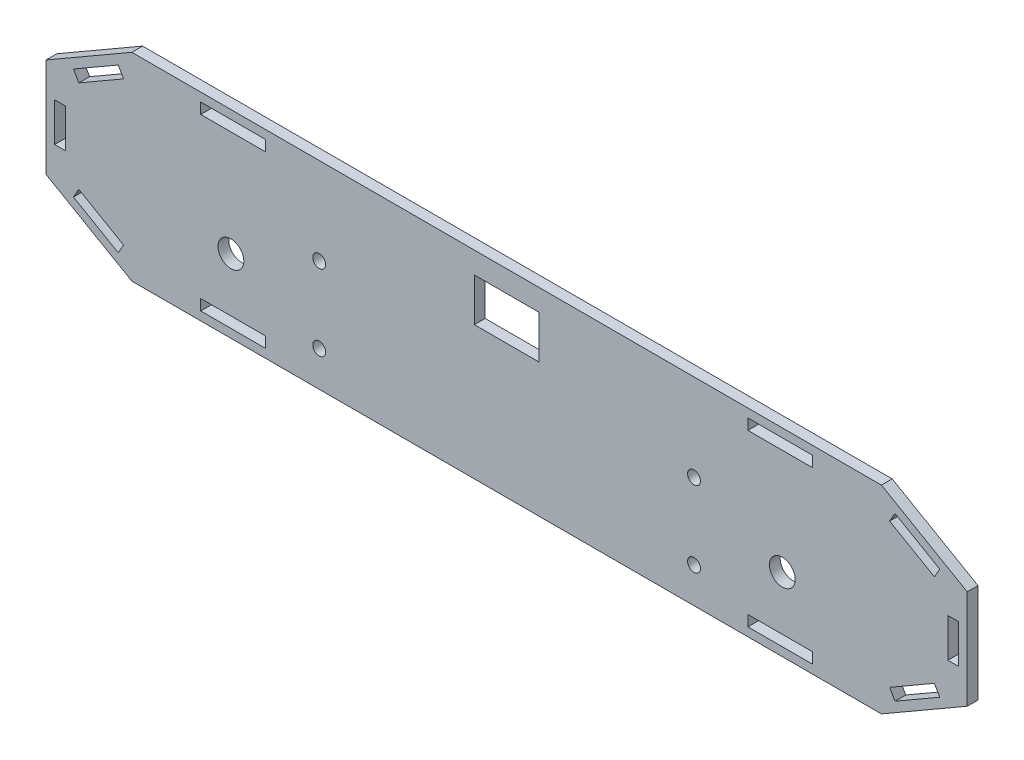
SolidWorks part; units mm, degrees
ref_plane "Front Plane" through (0, 0, 0) normal (0, 0, 1) x (1, 0, 0)
ref_plane "Top Plane" through (0, 0, 0) normal (0, 1, 0) x (1, 0, 0)
ref_plane "Right Plane" through (0, 0, 0) normal (1, 0, 0) x (0, 0, -1)
sketch "Sketch1" plane through (0, 0, 0) normal (0, 0, 1) x (1, 0, 0)
  line L0 (-87, 0) -> (87, 0) construction
  line L1 (-87, 23) -> (87, 23)
  line L2 (-87, -23) -> (87, -23)
  line L3 (0, 0) -> (0, 23) construction
  line L4 (-87, 23) -> (-106.9186, 11.5)
  line L5 (-106.9186, 11.5) -> (-106.9186, -11.5)
  line L6 (-106.9186, -11.5) -> (-87, -23)
  line L7 (-87, -23) -> (-87, 23) construction
  line L8 (106.9186, -11.5) -> (87, -23)
  line L9 (106.9186, 11.5) -> (106.9186, -11.5)
  line L10 (87, 23) -> (106.9186, 11.5)
  line L11 (87, -23) -> (87, 23) construction
  line L12 (-64, -6) -> (64, -6) construction
  arc A0 (-87, 23) -> (-87, -23) centre (-87, 0) ccw
  arc A1 (87, -23) -> (87, 23) centre (87, 0) ccw
  circle A2 centre (-43.5, 2.8) radius 1.5
  circle A3 centre (-43.5, -14.8) radius 1.5
  circle A4 centre (-64, -6) radius 3
  circle A7 centre (64, -6) radius 3
  circle A8 centre (43.5, 2.8) radius 1.5
  circle A9 centre (43.5, -14.8) radius 1.5
  point P2 (0, 0)
  point P8 (-110, 0)
  point P9 (110, 0)
  dimension "D3" = 3
  dimension "D4" = 3
  dimension "D7" = 6
  dimension "D1" = 46
  dimension "D2" = 220
  dimension "D5" = 17.6
  dimension "D6" = 20.5
  dimension "D8" = 23
  dimension "D9" = 23
  dimension "D10" = 23
  dimension "D11" = 6
extrude "Boss-Extrude1" add sketch "Sketch1" along normal blind 2.5 contours L10 L1 L4 L5 L6 L2 L8 L9 A9 A2 A3 A4 A8 A7
sketch "Sketch2" plane through (0, 0, 2.5) normal (0, 0, 1) x (1, 0, 0)
  line L0 (-71, 19.75) -> (-56, 19.75) construction
  line L1 (-71, 21) -> (-56, 21)
  line L2 (-71, 18.5) -> (-56, 18.5)
  line L3 (-87, 23) -> (87, 23) construction
  line L4 (0, 0) -> (0, 23) construction
  line L5 (71, 19.75) -> (56, 19.75) construction
  line L6 (71, 21) -> (56, 21)
  line L7 (71, 18.5) -> (56, 18.5)
  line L8 (0, 0) -> (26.1933, 0) construction
  line L9 (71, -19.75) -> (56, -19.75) construction
  line L10 (71, -21) -> (56, -21)
  line L11 (71, -18.5) -> (56, -18.5)
  line L12 (-71, -19.75) -> (-56, -19.75) construction
  line L13 (-71, -21) -> (-56, -21)
  line L14 (-71, -18.5) -> (-56, -18.5)
  line L15 (-71, 18.5) -> (-71, 21)
  line L16 (-56, 18.5) -> (-56, 21)
  line L17 (56, 18.5) -> (56, 21)
  line L18 (71, 18.5) -> (71, 21)
  line L19 (71, -21) -> (71, -18.5)
  line L20 (56, -21) -> (56, -18.5)
  line L21 (-71, -21) -> (-71, -18.5)
  line L22 (-56, -21) -> (-56, -18.5)
  arc A0 (-71, 21) -> (-71, 18.5) centre (-71, 19.75) ccw
  arc A1 (-56, 18.5) -> (-56, 21) centre (-56, 19.75) ccw
  arc A2 (71, 21) -> (71, 18.5) centre (71, 19.75) cw
  arc A3 (56, 18.5) -> (56, 21) centre (56, 19.75) cw
  arc A4 (71, -21) -> (71, -18.5) centre (71, -19.75) ccw
  arc A5 (56, -18.5) -> (56, -21) centre (56, -19.75) ccw
  arc A6 (-71, -21) -> (-71, -18.5) centre (-71, -19.75) cw
  arc A7 (-56, -18.5) -> (-56, -21) centre (-56, -19.75) cw
  point P2 (-63.5, 19.75)
  point P16 (63.5, 19.75)
  point P24 (63.5, -19.75)
  point P31 (-63.5, -19.75)
  dimension "D1" = 15
  dimension "D2" = 2.5
  dimension "D3" = 2
  dimension "D4" = 16
extrude "Cut-Extrude1" cut sketch "Sketch2" against normal blind 3 contours L2 L16 L1 L15 | L13 L22 L14 L21 | L20 L10 L19 L11 | L7 L18 L6 L17
sketch "Sketch3" plane through (0, 0, 2.5) normal (0, 0, 1) x (1, 0, 0)
  line L0 (-87, 20.6906) -> (-83.4467, 22.7421) construction
  line L1 (-100.5436, 12.8712) -> (-99.2936, 10.7061)
  line L2 (-90.1513, 18.8712) -> (-88.9013, 16.7061)
  line L3 (-87, 23) -> (-106.9186, 11.5) construction
  line L4 (-89.5263, 17.7887) -> (-99.9186, 11.7887) construction
  line L5 (-88.9013, 16.7061) -> (-99.2936, 10.7061)
  line L6 (-90.1513, 18.8712) -> (-100.5436, 12.8712)
  line L7 (-106.9186, 11.5) -> (-106.9186, -11.5) construction
  line L8 (0, 0) -> (0, 23) construction
  line L9 (-87, 23) -> (87, 23) construction
  line L10 (0, 0) -> (38.236, 0) construction
  line L11 (89.5263, 17.7887) -> (99.9186, 11.7887) construction
  line L12 (88.9013, 16.7061) -> (99.2936, 10.7061)
  line L13 (90.1513, 18.8712) -> (100.5436, 12.8712)
  line L14 (89.5263, -17.7887) -> (99.9186, -11.7887) construction
  line L15 (88.9013, -16.7061) -> (99.2936, -10.7061)
  line L16 (90.1513, -18.8712) -> (100.5436, -12.8712)
  line L17 (-89.5263, -17.7887) -> (-99.9186, -11.7887) construction
  line L18 (-88.9013, -16.7061) -> (-99.2936, -10.7061)
  line L19 (-90.1513, -18.8712) -> (-100.5436, -12.8712)
  line L20 (-99.2936, -10.7061) -> (-100.5436, -12.8712)
  line L21 (-88.9013, -16.7061) -> (-90.1513, -18.8712)
  line L22 (88.9013, -16.7061) -> (90.1513, -18.8712)
  line L23 (99.2936, -10.7061) -> (100.5436, -12.8712)
  line L24 (90.1513, 18.8712) -> (88.9013, 16.7061)
  line L25 (100.5436, 12.8712) -> (99.2936, 10.7061)
  arc A0 (-88.9013, 16.7061) -> (-90.1513, 18.8712) centre (-89.5263, 17.7887) ccw
  arc A1 (-100.5436, 12.8712) -> (-99.2936, 10.7061) centre (-99.9186, 11.7887) ccw
  arc A2 (88.9013, 16.7061) -> (90.1513, 18.8712) centre (89.5263, 17.7887) cw
  arc A3 (100.5436, 12.8712) -> (99.2936, 10.7061) centre (99.9186, 11.7887) cw
  arc A4 (88.9013, -16.7061) -> (90.1513, -18.8712) centre (89.5263, -17.7887) ccw
  arc A5 (100.5436, -12.8712) -> (99.2936, -10.7061) centre (99.9186, -11.7887) ccw
  arc A6 (-88.9013, -16.7061) -> (-90.1513, -18.8712) centre (-89.5263, -17.7887) cw
  arc A7 (-100.5436, -12.8712) -> (-99.2936, -10.7061) centre (-99.9186, -11.7887) cw
  point P6 (-94.7224, 14.7887)
  point P22 (94.7224, 14.7887)
  point P29 (94.7224, -14.7887)
  point P36 (-94.7224, -14.7887)
  dimension "D1" = 2.5
  dimension "D2" = 2
  dimension "D3" = 12
  dimension "D4" = 7
extrude "Cut-Extrude2" cut sketch "Sketch3" against normal blind 3 contours L2 L6 L1 L5 | L21 L18 L20 L19 | L23 L15 L22 L16 | L25 L13 L24 L12
sketch "Sketch4" plane through (0, 0, 2.5) normal (0, 0, 1) x (1, 0, 0)
  line L0 (-103.6686, 4.5) -> (-103.6686, -4.5) construction
  line L1 (-102.4186, 4.5) -> (-102.4186, -4.5)
  line L2 (-104.9186, 4.5) -> (-104.9186, -4.5)
  line L3 (-106.9186, 11.5) -> (-106.9186, -11.5) construction
  line L4 (0, 0) -> (0, 37.0827) construction
  line L5 (103.6686, 4.5) -> (103.6686, -4.5) construction
  line L6 (102.4186, 4.5) -> (102.4186, -4.5)
  line L7 (104.9186, 4.5) -> (104.9186, -4.5)
  line L8 (-104.9186, -4.5) -> (-102.4186, -4.5)
  line L9 (-102.4186, 4.5) -> (-104.9186, 4.5)
  line L10 (102.4186, 4.5) -> (104.9186, 4.5)
  line L11 (104.9186, -4.5) -> (102.4186, -4.5)
  arc A0 (-102.4186, 4.5) -> (-104.9186, 4.5) centre (-103.6686, 4.5) ccw
  arc A1 (-104.9186, -4.5) -> (-102.4186, -4.5) centre (-103.6686, -4.5) ccw
  arc A2 (102.4186, 4.5) -> (104.9186, 4.5) centre (103.6686, 4.5) cw
  arc A3 (104.9186, -4.5) -> (102.4186, -4.5) centre (103.6686, -4.5) cw
  point P2 (-103.6686, 0)
  point P15 (103.6686, 0)
  dimension "D2" = 9
  dimension "D1" = 2.5
  dimension "D3" = 2
extrude "Cut-Extrude3" cut sketch "Sketch4" against normal blind 12 contours L1 L9 L2 L8 | L11 L7 L10 L6
sketch "Sketch5" plane through (0, 0, 2.5) normal (0, 0, 1) x (1, 0, 0)
  line L0 (-87, 23) -> (87, 23) construction
  line L1 (-7.5, 18) -> (7.5, 18)
  line L2 (-7.5, 18) -> (-7.5, 8)
  line L3 (-7.5, 8) -> (7.5, 8)
  line L4 (7.5, 18) -> (7.5, 8)
  point P4 (0, 8)
  point P8 (0, 23)
  dimension "D1" = 15
  dimension "D2" = 10
  dimension "D3" = 5
extrude "Cut-Extrude4" cut sketch "Sketch5" against normal blind 2.5
